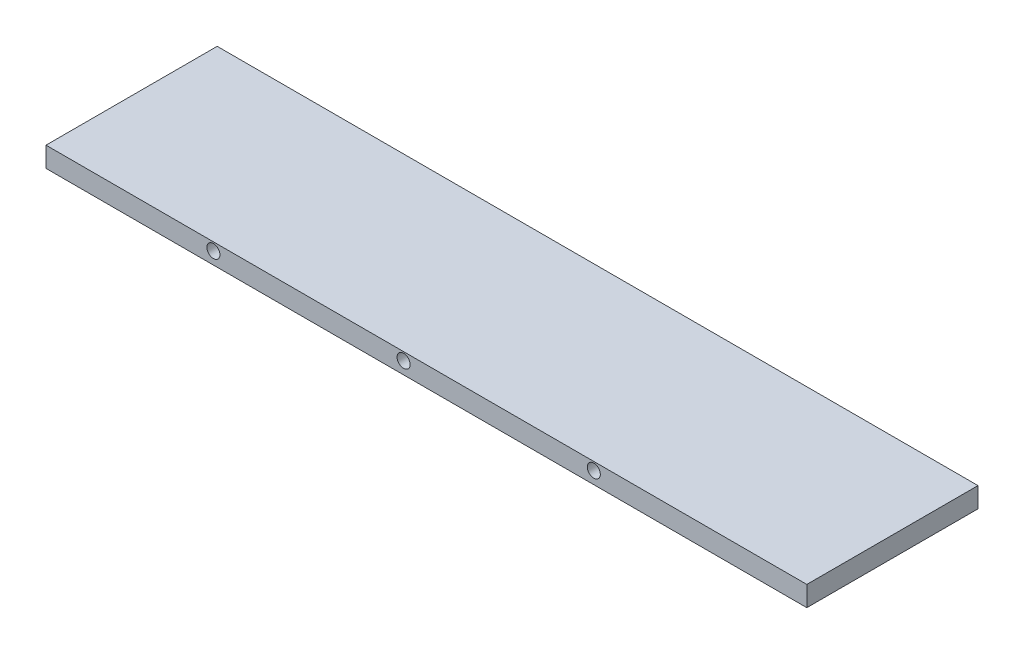
SolidWorks part; units mm, degrees
ref_plane "Front Plane" through (0, 0, 0) normal (0, 0, 1) x (1, 0, 0)
ref_plane "Top Plane" through (0, 0, 0) normal (0, 1, 0) x (1, 0, 0)
ref_plane "Right Plane" through (0, 0, 0) normal (1, 0, 0) x (0, 0, -1)
sketch "Sketch1" plane through (0, 0, 0) normal (0, 1, 0) x (1, 0, 0)
  line L1 (-34.0308, 14.4884) -> (219.9692, 14.4884)
  line L2 (-34.0308, 14.4884) -> (-34.0308, -42.6616)
  line L3 (-34.0308, -42.6616) -> (219.9692, -42.6616)
  line L4 (219.9692, 14.4884) -> (219.9692, -42.6616)
  circle A3 centre (202.9692, 0.5184) radius 10
  circle A4 centre (171.2192, 0.5184) radius 10
  circle A5 centre (139.4692, 0.5184) radius 10
  circle A6 centre (107.7192, 0.5184) radius 10
  circle A7 centre (75.9692, 0.5184) radius 10
  circle A8 centre (44.2192, 0.5184) radius 10
  circle A10 centre (171.2192, -22.3416) radius 10
  circle A11 centre (139.4692, -22.3416) radius 10
  circle A12 centre (107.7192, -22.3416) radius 10
  circle A13 centre (75.9692, -22.3416) radius 10
  circle A14 centre (44.2192, -22.3416) radius 10
  circle A16 centre (202.9692, -22.3416) radius 10
  circle A17 centre (12.4692, 0.5184) radius 10
  circle A18 centre (-19.2808, 0.5184) radius 10
  circle A19 centre (12.4692, -22.3416) radius 10
  circle A20 centre (-19.2808, -22.3416) radius 10
  dimension "D3" = 8
  dimension "D5" = 13.97
  dimension "D7" = 22.86
  dimension "D9" = 20
  dimension "D1" = 254
  dimension "D2" = 57.15
  dimension "D4" = 2
  dimension "D6" = 31.75
  dimension "D10" = 17
extrude "Boss-Extrude1" add sketch "Sketch1" along normal blind 6.73
sketch "Sketch25" plane through (0, 0, 0) normal (0, -1, 0) x (1, 0, 0)
  line L0 (-34.0308, -14.4884) -> (-34.0308, 42.6616) construction
  circle A0 centre (44.2192, 22.3416) radius 10.25
  circle A1 centre (75.9692, 22.3416) radius 10.25
  circle A2 centre (107.7192, 22.3416) radius 10.25
  circle A3 centre (139.4692, 22.3416) radius 10.25
  circle A4 centre (171.2192, 22.3416) radius 10.25
  circle A5 centre (202.9692, 22.3416) radius 10.25
  circle A6 centre (75.9692, -0.5184) radius 10.25
  circle A7 centre (107.7192, -0.5184) radius 10.25
  circle A8 centre (139.4692, -0.5184) radius 10.25
  circle A9 centre (171.2192, -0.5184) radius 10.25
  circle A10 centre (202.9692, -0.5184) radius 10.25
  circle A11 centre (44.2192, -0.5184) radius 10.25
  circle A16 centre (12.4692, 22.3416) radius 10.25
  circle A17 centre (-19.2808, 22.3416) radius 10.25
  circle A18 centre (-19.2808, -0.5184) radius 10.25
  circle A19 centre (12.4692, -0.5184) radius 10.25
  dimension "D1" = 20.5
  dimension "D7" = 20.5
  dimension "D4" = 78.25
  dimension "D5" = 22.86
  dimension "D6" = 31.75
  dimension "D2" = 6
  dimension "D3" = 2
  dimension "D8" = 2
  dimension "D9" = 2
extrude "Cut-Extrude1" cut sketch "Sketch25" against normal blind 7.6
sketch "Sketch3" plane through (0, 0, -14.4884) normal (0, 0, -1) x (-1, 0, 0)
  line L3 (34.0308, 6.73) -> (34.0308, 0) construction
  line L5 (-219.9692, 0) -> (34.0308, 0) construction
  point P0 (-148.8492, 4.064)
  point P6 (-21.8492, 4.064)
  point P7 (-21.8492, 4.064)
  point P8 (-85.3492, 4.064)
  point P10 (-219.9692, 3.5476)
  dimension "D1" = 4.064
  dimension "D2" = 63.5
  dimension "D4" = 63.5
  dimension "D5" = 55.88
  dimension "D3" = 3
sketch "Sketch26" plane through (0, 6.73, 0) normal (0, 1, 0) x (1, 0, 0)
  line L1 (-34.0308, 14.4884) -> (219.9692, 14.4884)
  line L2 (-34.0308, 14.4884) -> (-34.0308, -42.6616)
  line L3 (-34.0308, -42.6616) -> (219.9692, -42.6616)
  line L4 (219.9692, 14.4884) -> (219.9692, -42.6616)
extrude "Boss-Extrude2" add sketch "Sketch26" against normal blind 0.4
sketch "Sketch4" plane through (0, 0, 42.6616) normal (0, 0, 1) x (1, 0, 0)
  line L0 (-34.0308, 0) -> (219.9692, 0) construction
  line L2 (-34.0308, 6.73) -> (-34.0308, 0) construction
  point P5 (21.8492, 4.064)
  point P6 (148.8492, 4.064)
  point P8 (82.8092, 2.032)
  point P12 (85.3492, 4.064)
  dimension "D1" = 4.064
  dimension "D2" = 55.88
  dimension "D3" = 63.5
  dimension "D4" = 63.5
hole_wizard "11/64 (0.17188) Diameter Hole1" positions "Sketch15" profile "Sketch16" hole size "11/64" standard "ANSI Inch"
sketch "Sketch15" plane through (0, 0, 42.6616) normal (0, 0, 1) x (1, 0, 0)
  point P0 (21.8492, 4.064)
  point P9 (148.8492, 4.064)
  point P12 (85.3492, 4.064)
sketch "Sketch16" plane through (21.8492, 4.064, 42.6616) normal (1, 0, 0) x (0, -1, 0)
  line L0 (0, 0) -> (0, 7.6616)
  line L1 (0, 7.6616) -> (2.1829, 6.35)
  line L2 (2.1829, 6.35) -> (2.1829, 0)
  line L5 (2.1829, 0) -> (0, 0)
  line L10 (0, 7.6616) -> (-2.1829, 6.35) construction
  line L11 (0, -6.35) -> (0, 107.95) construction
  dimension "Hole Dia." = 4.3658
  dimension "Hole Depth" = 6.35
  dimension "Drill Angle" = 118
hole_wizard "11/64 (0.17188) Diameter Hole2" positions "Sketch23" profile "Sketch24" hole size "11/64" standard "ANSI Inch"
sketch "Sketch23" plane through (0, 0, -14.4884) normal (0, 0, -1) x (-1, 0, 0)
  point P0 (-148.8492, 4.064)
  point P3 (-85.3492, 4.064)
  point P15 (-21.8492, 4.064)
sketch "Sketch24" plane through (148.8492, 4.064, -14.4884) normal (1, 0, 0) x (0, 1, 0)
  line L0 (0, 0) -> (0, 7.6616)
  line L1 (0, 7.6616) -> (2.1829, 6.35)
  line L2 (2.1829, 6.35) -> (2.1829, 0)
  line L5 (2.1829, 0) -> (0, 0)
  line L10 (0, 7.6616) -> (-2.1829, 6.35) construction
  line L11 (0, -6.35) -> (0, 107.95) construction
  dimension "Hole Dia." = 4.3658
  dimension "Hole Depth" = 6.35
  dimension "Drill Angle" = 118
